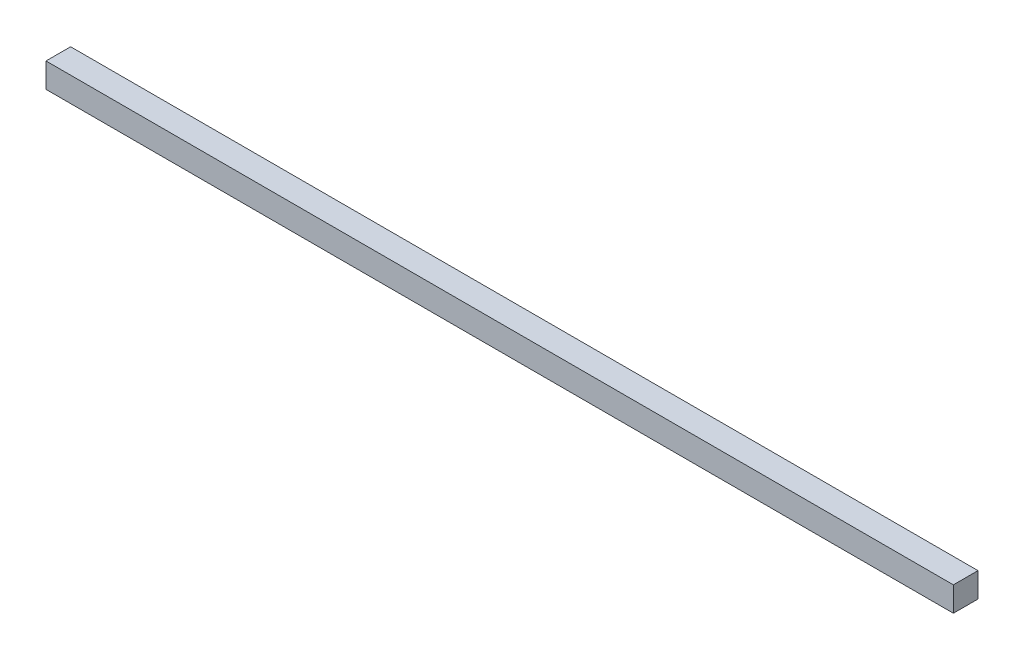
SolidWorks part; units mm, degrees
ref_plane "Front Plane" through (0, 0, 0) normal (0, 0, 1) x (1, 0, 0)
ref_plane "Top Plane" through (0, 0, 0) normal (0, 1, 0) x (1, 0, 0)
ref_plane "Right Plane" through (0, 0, 0) normal (1, 0, 0) x (0, 0, -1)
sketch "Sketch1" plane through (0, 0, 0) normal (0, 0, 1) x (1, 0, 0)
  line L1 (0, 0) -> (740, 0)
  line L2 (0, 0) -> (0, 20)
  line L3 (0, 20) -> (740, 20)
  line L4 (740, 0) -> (740, 20)
  dimension "D1" = 740
  dimension "D2" = 20
extrude "Boss-Extrude1" add sketch "Sketch1" along normal blind 20
sketch "Sketch2" plane through (0, 0, 20) normal (0, 0, 1) x (1, 0, 0)
  line L0 (740, 20) -> (0, 20) construction
  line L1 (740, 0) -> (737, 0)
  line L2 (740, 0) -> (740, 20)
  line L3 (740, 20) -> (737, 20)
  line L4 (737, 0) -> (737, 20)
  line L5 (737, 12.7206) -> (737, 34.0042) construction
extrude "Cut-Extrude1" cut sketch "Sketch2" against normal through all both and the other way through all contours L2 L1 L4 L3
